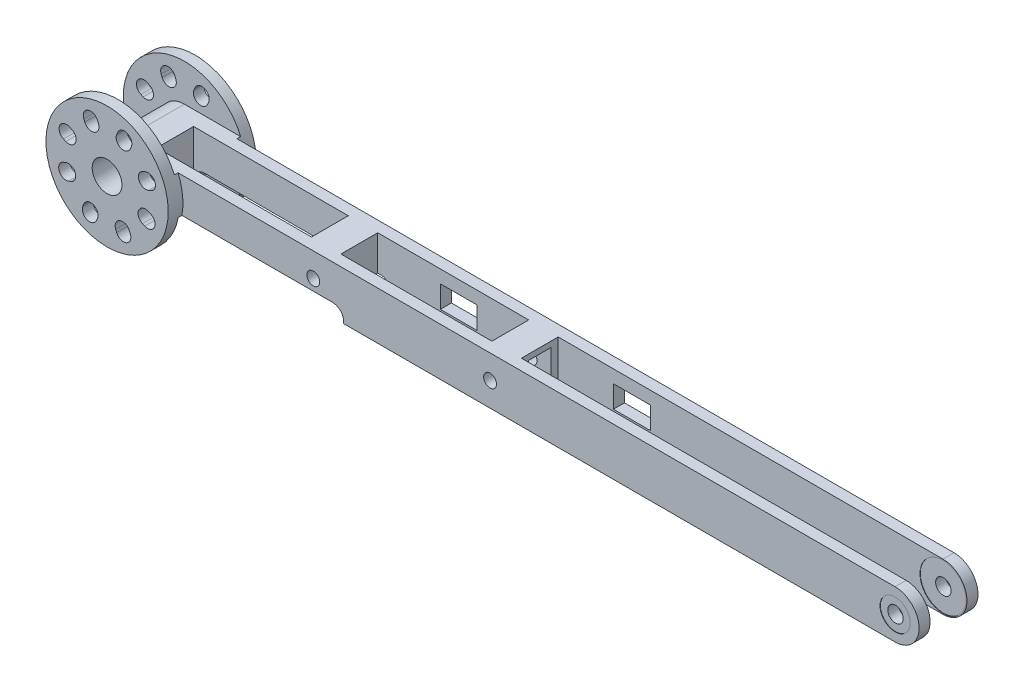
SolidWorks part; units mm, degrees
ref_plane "前视基准面" through (0, 0, 0) normal (0, 0, 1) x (1, 0, 0)
ref_plane "上视基准面" through (0, 0, 0) normal (0, 1, 0) x (1, 0, 0)
ref_plane "右视基准面" through (0, 0, 0) normal (1, 0, 0) x (0, 0, -1)
sketch "草图1" plane through (0, 0, 0) normal (0, 0, 1) x (1, 0, 0)
  line L0 (0, 0) -> (21.75, 0) construction
  line L1 (0, 6.5) -> (210, 6.5)
  line L2 (0, -6.5) -> (210, -6.5)
  line L3 (21.75, 0) -> (210, 0) construction
  arc A0 (0, 6.5) -> (0, -6.5) centre (0, 0) ccw
  arc A1 (210, -6.5) -> (210, 6.5) centre (210, 0) ccw
  circle A2 centre (0, 0) radius 4.04
  circle A3 centre (100, 0) radius 1.75
  circle A4 centre (210, 0) radius 2.1
  circle A10 centre (52, 0) radius 1.75
  point P3 (100, 0)
  dimension "D2" = 13
  dimension "D3" = 8.08
  dimension "D4" = 3.5
  dimension "D5" = 4.2
  dimension "D6" = 6.5
  dimension "D1" = 210
extrude "凸台-拉伸1" add sketch "草图1" against normal blind 16
sketch "草图2" plane through (0, -6.5, 0) normal (0, -1, 0) x (1, 0, 0)
  line L0 (148.5, -3) -> (153.5, -3)
  line L1 (148.5, -13) -> (153.5, -13)
  line L4 (0, 0) -> (0, -16) construction
  line L6 (6.5, -3) -> (6.5, -13)
  line L7 (0, 0) -> (210, 0) construction
  line L8 (0, -16) -> (210, -16) construction
  line L9 (6.5, -3) -> (48.5, -3)
  line L10 (216.5, -16) -> (216.5, 0) construction
  line L11 (216.5, -3) -> (216.5, -13)
  line L12 (216.5, -13) -> (153.5, -13)
  line L13 (48.5, -3) -> (48.5, -13)
  line L14 (56.5, -3) -> (56.5, -13)
  line L15 (97.5, -3) -> (97.5, -13)
  line L16 (105.5, -3) -> (105.5, -13)
  line L19 (56.5, -3) -> (97.5, -3)
  line L20 (48.5, -13) -> (6.5, -13)
  line L21 (97.5, -13) -> (56.5, -13)
  line L22 (105.5, -3) -> (148.5, -3)
  line L23 (148.5, -13) -> (105.5, -13)
  line L24 (153.5, -3) -> (216.5, -3)
  dimension "D1" = 6.5
  dimension "D2" = 3
  dimension "D3" = 3
  dimension "D6" = 8
  dimension "D7" = 8
  dimension "D8" = 42
  dimension "D9" = 41
extrude "切除-拉伸1" cut sketch "草图2" against normal through all
sketch "草图6" plane through (0, -6.5, 0) normal (0, -1, 0) x (1, 0, 0)
  line L0 (6.5, 0) -> (6.5, -16)
  line L1 (0, 0) -> (210, 0) construction
  line L2 (0, -16) -> (210, -16) construction
  line L3 (6.5, -16) -> (60.2558, -16)
  line L4 (60.2558, -16) -> (60.2558, 0)
  line L5 (60.2558, 0) -> (6.5, 0)
extrude "切除-拉伸2" cut sketch "草图6" against normal blind 3.5
fillet "圆角1" radius 3 4 edges at (60.2558, -3, -1.5) (60.2558, -3, -14.5) (6.5, -3, -1.5) (6.5, -3, -14.5)
sketch "草图7" plane through (0, 0, 0) normal (0, 0, 1) x (1, 0, 0)
  circle A1 centre (0, 0) radius 6.5
  circle A2 centre (0, 0) radius 4.04
extrude "凸台-拉伸2" add sketch "草图7" along normal blind 1
sketch "草图8" plane through (0, 0, 1) normal (0, 0, 1) x (1, 0, 0)
  line L1 (9.7632, 6.0564) -> (10.4005, 6.3111)
  line L15 (11.8851, 2.5969) -> (11.2479, 2.3421)
  line L31 (11.1861, -2.6211) -> (11.8169, -2.8916)
  line L33 (10.2403, -6.5678) -> (9.6096, -6.2973)
  line L35 (2.6211, 11.1861) -> (2.8916, 11.8169) construction
  line L38 (6.0564, -9.7632) -> (6.3111, -10.4005)
  line L47 (2.5969, -11.8851) -> (2.3421, -11.2479)
  line L49 (-2.6211, -11.1861) -> (-2.8916, -11.8169)
  line L63 (6.5678, 10.2403) -> (6.2973, 9.6096) construction
  line L64 (2.6211, 11.1861) -> (2.8916, 11.8169)
  line L65 (6.5678, 10.2403) -> (6.2973, 9.6096)
  line L66 (-6.5678, -10.2403) -> (-6.2973, -9.6096)
  line L67 (-9.7632, -6.0564) -> (-10.4005, -6.3111)
  line L68 (-11.8851, -2.5969) -> (-11.2479, -2.3421)
  line L69 (-11.1861, 2.6211) -> (-11.8169, 2.8916)
  line L70 (-10.2403, 6.5678) -> (-9.6096, 6.2973)
  line L71 (-6.0564, 9.7632) -> (-6.3111, 10.4005)
  line L72 (-2.5969, 11.8851) -> (-2.3421, 11.2479)
  arc A95 (3.9874, 12.8857) -> (2.8916, 11.8169) centre (4.7297, 11.0286) ccw construction
  arc A96 (6.5678, 10.2403) -> (3.9874, 12.8857) centre (4.7297, 11.0286) ccw construction
  arc A97 (2.6211, 11.1861) -> (6.2973, 9.6096) centre (4.4592, 10.3979) ccw construction
  arc A98 (3.9874, 12.8857) -> (2.8916, 11.8169) centre (4.7297, 11.0286) ccw
  arc A99 (6.5678, 10.2403) -> (3.9874, 12.8857) centre (4.7297, 11.0286) ccw
  arc A100 (2.6211, 11.1861) -> (6.2973, 9.6096) centre (4.4592, 10.3979) ccw
  circle A101 centre (0, 0) radius 4.04
  circle A102 centre (0, 0) radius 16.6
  arc A103 (11.8851, 2.5969) -> (11.9311, 6.2921) centre (11.1428, 4.454) ccw
  arc A104 (11.9311, 6.2921) -> (10.4005, 6.3111) centre (11.1428, 4.454) ccw
  arc A105 (9.7632, 6.0564) -> (11.2479, 2.3421) centre (10.5055, 4.1993) ccw
  arc A106 (10.2403, -6.5678) -> (12.8857, -3.9874) centre (11.0286, -4.7297) ccw
  arc A107 (12.8857, -3.9874) -> (11.8169, -2.8916) centre (11.0286, -4.7297) ccw
  arc A108 (11.1861, -2.6211) -> (9.6096, -6.2973) centre (10.3979, -4.4592) ccw
  arc A109 (2.5969, -11.8851) -> (6.2921, -11.9311) centre (4.454, -11.1428) ccw
  arc A110 (6.2921, -11.9311) -> (6.3111, -10.4005) centre (4.454, -11.1428) ccw
  arc A111 (6.0564, -9.7632) -> (2.3421, -11.2479) centre (4.1993, -10.5055) ccw
  arc A112 (-6.5678, -10.2403) -> (-3.9874, -12.8857) centre (-4.7297, -11.0286) ccw
  arc A113 (-3.9874, -12.8857) -> (-2.8916, -11.8169) centre (-4.7297, -11.0286) ccw
  arc A114 (-2.6211, -11.1861) -> (-6.2973, -9.6096) centre (-4.4592, -10.3979) ccw
  arc A115 (-11.8851, -2.5969) -> (-11.9311, -6.2921) centre (-11.1428, -4.454) ccw
  arc A116 (-11.9311, -6.2921) -> (-10.4005, -6.3111) centre (-11.1428, -4.454) ccw
  arc A117 (-9.7632, -6.0564) -> (-11.2479, -2.3421) centre (-10.5055, -4.1993) ccw
  arc A118 (-10.2403, 6.5678) -> (-12.8857, 3.9874) centre (-11.0286, 4.7297) ccw
  arc A119 (-12.8857, 3.9874) -> (-11.8169, 2.8916) centre (-11.0286, 4.7297) ccw
  arc A120 (-11.1861, 2.6211) -> (-9.6096, 6.2973) centre (-10.3979, 4.4592) ccw
  arc A121 (-2.5969, 11.8851) -> (-6.2921, 11.9311) centre (-4.454, 11.1428) ccw
  arc A122 (-6.2921, 11.9311) -> (-6.3111, 10.4005) centre (-4.454, 11.1428) ccw
  arc A123 (-6.0564, 9.7632) -> (-2.3421, 11.2479) centre (-4.1993, 10.5055) ccw
  point P62 (0, 0)
  dimension "D1" = 33.2
  dimension "D2" = 8.08
  dimension "D3" = 8
extrude "凸台-拉伸3" add sketch "草图8" along normal blind 3 separate body
sketch "草图9" plane through (0, 0, -16) normal (0, 0, -1) x (-1, 0, 0)
  circle A0 centre (0, 0) radius 4.04
  circle A1 centre (0, 0) radius 6.5
extrude "凸台-拉伸4" add sketch "草图9" along normal blind 1
sketch "草图10" plane through (0, 0, -17) normal (0, 0, -1) x (-1, 0, 0)
  line L1 (2.3421, 11.2479) -> (2.5969, 11.8851)
  line L5 (6.3111, 10.4005) -> (6.0564, 9.7632)
  line L9 (9.6096, 6.2973) -> (10.2403, 6.5678)
  line L11 (11.8169, 2.8916) -> (11.1861, 2.6211)
  line L13 (11.2479, -2.3421) -> (11.8851, -2.5969)
  line L15 (10.4005, -6.3111) -> (9.7632, -6.0564)
  line L28 (-6.2973, 9.6096) -> (-6.5678, 10.2403) construction
  line L29 (-2.8916, 11.8169) -> (-2.6211, 11.1861) construction
  line L30 (-6.2973, 9.6096) -> (-6.5678, 10.2403)
  line L31 (-2.8916, 11.8169) -> (-2.6211, 11.1861)
  line L32 (6.2973, -9.6096) -> (6.5678, -10.2403)
  line L33 (2.8916, -11.8169) -> (2.6211, -11.1861)
  line L34 (-2.3421, -11.2479) -> (-2.5969, -11.8851)
  line L35 (-6.3111, -10.4005) -> (-6.0564, -9.7632)
  line L36 (-9.6096, -6.2973) -> (-10.2403, -6.5678)
  line L37 (-11.8169, -2.8916) -> (-11.1861, -2.6211)
  line L38 (-11.2479, 2.3421) -> (-11.8851, 2.5969)
  line L39 (-10.4005, 6.3111) -> (-9.7632, 6.0564)
  circle A0 centre (0, 0) radius 16.6
  circle A1 centre (0, 0) radius 4.04
  arc A30 (2.3421, 11.2479) -> (6.0564, 9.7632) centre (4.1993, 10.5055) ccw
  arc A31 (-2.8916, 11.8169) -> (-6.5678, 10.2403) centre (-4.7297, 11.0286) ccw construction
  arc A32 (-6.2973, 9.6096) -> (-2.6211, 11.1861) centre (-4.4592, 10.3979) ccw construction
  arc A33 (-2.8916, 11.8169) -> (-6.5678, 10.2403) centre (-4.7297, 11.0286) ccw
  arc A34 (-6.2973, 9.6096) -> (-2.6211, 11.1861) centre (-4.4592, 10.3979) ccw
  arc A35 (6.3111, 10.4005) -> (2.5969, 11.8851) centre (4.454, 11.1428) ccw
  arc A36 (9.6096, 6.2973) -> (11.1861, 2.6211) centre (10.3979, 4.4592) ccw
  arc A37 (11.8169, 2.8916) -> (10.2403, 6.5678) centre (11.0286, 4.7297) ccw
  arc A38 (11.2479, -2.3421) -> (9.7632, -6.0564) centre (10.5055, -4.1993) ccw
  arc A39 (10.4005, -6.3111) -> (11.8851, -2.5969) centre (11.1428, -4.454) ccw
  arc A40 (6.2973, -9.6096) -> (2.6211, -11.1861) centre (4.4592, -10.3979) ccw
  arc A41 (2.8916, -11.8169) -> (6.5678, -10.2403) centre (4.7297, -11.0286) ccw
  arc A42 (-2.3421, -11.2479) -> (-6.0564, -9.7632) centre (-4.1993, -10.5055) ccw
  arc A43 (-6.3111, -10.4005) -> (-2.5969, -11.8851) centre (-4.454, -11.1428) ccw
  arc A44 (-9.6096, -6.2973) -> (-11.1861, -2.6211) centre (-10.3979, -4.4592) ccw
  arc A45 (-11.8169, -2.8916) -> (-10.2403, -6.5678) centre (-11.0286, -4.7297) ccw
  arc A46 (-11.2479, 2.3421) -> (-9.7632, 6.0564) centre (-10.5055, 4.1993) ccw
  arc A47 (-10.4005, 6.3111) -> (-11.8851, 2.5969) centre (-11.1428, 4.454) ccw
  point P54 (0, 0)
  dimension "D1" = 8
extrude "凸台-拉伸5" add sketch "草图10" along normal blind 2.9
sketch "草图11" plane through (0, 0, 0) normal (0, 0, 1) x (1, 0, 0)
  line L6 (0, -6.5) -> (6.5, -6.5)
  line L7 (6.5, -6.5) -> (6.5, -6)
  line L8 (9.5, -3) -> (57.2558, -3)
  line L9 (60.2558, -6) -> (60.2558, -6.5)
  line L10 (60.2558, -6.5) -> (210, -6.5)
  line L11 (210, 6.5) -> (0, 6.5)
  line L12 (0, -6.5) -> (6.5, -6.5)
  line L13 (6.5, -6.5) -> (6.5, -6)
  line L14 (9.5, -3) -> (16.3267, -3)
  line L17 (15.2745, 6.5) -> (0, 6.5)
  arc A0 (16.3267, -3) -> (15.2745, 6.5) centre (0, 0) ccw
  arc A4 (0, -6.5) -> (0, 6.5) centre (0, 0) ccw
  arc A5 (9.5, -3) -> (6.5, -6) centre (9.5, -6) ccw
  arc A6 (60.2558, -6) -> (57.2558, -3) centre (57.2558, -6) ccw
  arc A7 (210, -6.5) -> (210, 6.5) centre (210, 0) ccw
  arc A8 (0, -6.5) -> (0, 6.5) centre (0, 0) ccw
  arc A9 (9.5, -3) -> (6.5, -6) centre (9.5, -6) ccw
  dimension "D1" = 0
extrude "凸台-拉伸7" add sketch "草图11" along normal blind 1
sketch "草图12" plane through (0, 0, -16) normal (0, 0, -1) x (-1, 0, 0)
  line L6 (0, 6.5) -> (-210, 6.5)
  line L7 (-210, -6.5) -> (-60.2558, -6.5)
  line L8 (-60.2558, -6.5) -> (-60.2558, -6)
  line L9 (-57.2558, -3) -> (-9.5, -3)
  line L10 (-6.5, -6) -> (-6.5, -6.5)
  line L11 (-6.5, -6.5) -> (0, -6.5)
  line L12 (0, 6.5) -> (-15.2745, 6.5)
  line L15 (-16.3267, -3) -> (-9.5, -3)
  line L16 (-6.5, -6) -> (-6.5, -6.5)
  line L17 (-6.5, -6.5) -> (0, -6.5)
  arc A0 (-15.2745, 6.5) -> (-16.3267, -3) centre (0, 0) ccw
  arc A4 (0, 6.5) -> (0, -6.5) centre (0, 0) ccw
  arc A5 (-210, 6.5) -> (-210, -6.5) centre (-210, 0) ccw
  arc A6 (-57.2558, -3) -> (-60.2558, -6) centre (-57.2558, -6) ccw
  arc A7 (-6.5, -6) -> (-9.5, -3) centre (-9.5, -6) ccw
  arc A8 (0, 6.5) -> (0, -6.5) centre (0, 0) ccw
  arc A11 (-6.5, -6) -> (-9.5, -3) centre (-9.5, -6) ccw
  dimension "D1" = 0
extrude "凸台-拉伸8" add sketch "草图12" along normal blind 1
sketch "草图13" plane through (0, 0, -16) normal (0, 0, -1) x (-1, 0, 0)
  line L2 (-130.5, 3) -> (-120.5, 3)
  line L3 (-83.5, 3) -> (-73.5, 3)
  line L4 (-83.5, 3) -> (-83.5, -3)
  line L5 (-83.5, -3) -> (-73.5, -3)
  line L6 (-73.5, 3) -> (-73.5, -3)
  line L7 (-130.5, 3) -> (-130.5, -3)
  line L8 (-130.5, -3) -> (-120.5, -3)
  line L9 (-120.5, 3) -> (-120.5, -3)
  dimension "D5" = 10
  dimension "D6" = 6
extrude "切除-拉伸3" cut sketch "草图13" against normal blind 10
sketch "草图14" plane through (105.5, 0, 0) normal (1, 0, 0) x (0, 0, -1)
  line L0 (3, 6.5) -> (13, 6.5) construction
  line L1 (5, 5) -> (11, 5)
  line L2 (5, 5) -> (5, -5)
  line L3 (5, -5) -> (11, -5)
  line L4 (11, 5) -> (11, -5)
  line L6 (3, 6.5) -> (3, -6.5) construction
  dimension "D2" = 10
  dimension "D3" = 6
  dimension "D5" = 1.5
  dimension "D6" = 2
extrude "切除-拉伸4" cut sketch "草图14" against normal blind 10
sketch "草图15" plane through (0, 0, 0) normal (0, 0, 1) x (1, 0, 0)
  circle A0 centre (210, 0) radius 4.1
extrude "下轴_外侧A_让位0p1" cut sketch "草图15" against normal blind 0.1
sketch "草图16" plane through (0, 0, -16) normal (0, 0, -1) x (-1, 0, 0)
  circle A0 centre (-210, 0) radius 4.1
extrude "下轴_外侧B_让位0p1" cut sketch "草图16" against normal blind 0.1
sketch "草图17" plane through (0, 0, -3) normal (0, 0, -1) x (-1, 0, 0)
  circle A0 centre (-210, 0) radius 6.25
extrude "下轴_内侧A_让位0p1" cut sketch "草图17" against normal blind 0.1
sketch "草图18" plane through (0, 0, -13) normal (0, 0, 1) x (1, 0, 0)
  circle A0 centre (210, 0) radius 6.25
extrude "下轴_内侧B_让位0p1" cut sketch "草图18" against normal blind 0.1
